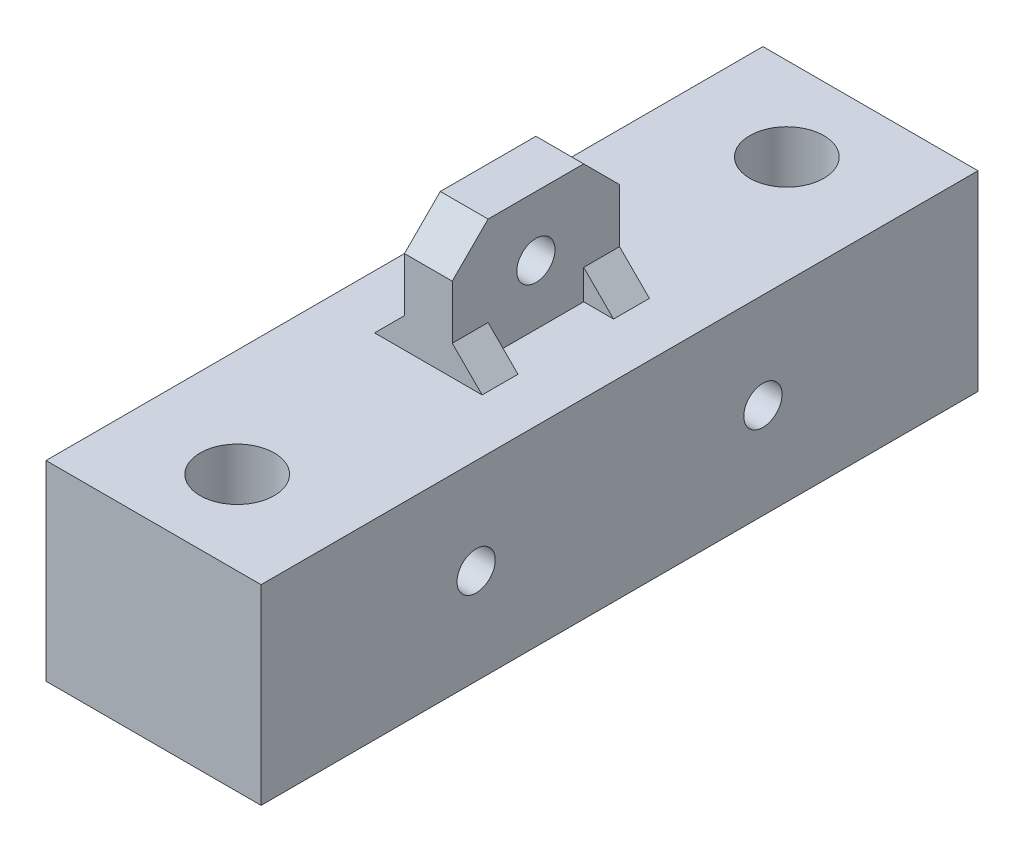
SolidWorks part; units mm, degrees
ref_plane "Front Plane" through (0, 0, 0) normal (0, 0, 1) x (1, 0, 0)
ref_plane "Top Plane" through (0, 0, 0) normal (0, 1, 0) x (1, 0, 0)
ref_plane "Right Plane" through (0, 0, 0) normal (1, 0, 0) x (0, 0, -1)
sketch "Sketch1" plane through (0, 0, 0) normal (0, 1, 0) x (1, 0, 0)
  line L1 (-9, -30) -> (9, -30)
  line L2 (-9, -30) -> (-9, 30)
  line L3 (-9, 30) -> (9, 30)
  line L4 (9, -30) -> (9, 30)
  line L5 (-9, -30) -> (9, 30) construction
  line L6 (-9, 30) -> (9, -30) construction
  point P0 (0, 0)
  dimension "D1" = 18
  dimension "D2" = 60
extrude "Boss-Extrude1" add sketch "Sketch1" along normal blind 16
sketch "Sketch2" plane through (0, 16, 0) normal (0, 1, 0) x (1, 0, 0)
  line L0 (9, 30) -> (-9, 30) construction
  line L1 (-9, -30) -> (9, -30) construction
  circle A0 centre (0, 23) radius 3.1
  circle A1 centre (0, -23) radius 3.1
  point P4 (0, 0)
  point P5 (0, 0)
  point P10 (0, 0)
  dimension "D1" = 6.2
  dimension "D2" = 6.2
  dimension "D3" = 7
  dimension "D4" = 7
extrude "Cut-Extrude1" cut sketch "Sketch2" against normal through all
sketch "Sketch3" plane through (-9, 0, 0) normal (-1, 0, 0) x (0, 0, 1)
  line L0 (-30, 0) -> (30, 0) construction
  line L1 (-30, 16) -> (-30, 0) construction
  line L3 (30, 16) -> (30, 0) construction
  circle A0 centre (-12, 8) radius 1.6
  circle A1 centre (12, 8) radius 1.6
  point P4 (0, 0)
  point P9 (-30.3857, 11.9209)
  dimension "D3" = 3.2
  dimension "D4" = 3.2
  dimension "D5" = 18
  dimension "D1" = 8
  dimension "D2" = 18
extrude "Cut-Extrude2" cut sketch "Sketch3" against normal through all
sketch "Sketch4" plane through (0, 16, 0) normal (0, 1, 0) x (1, 0, 0)
  line L1 (-2, -7) -> (2, -7)
  line L2 (-2, -7) -> (-2, 7)
  line L3 (-2, 7) -> (2, 7)
  line L4 (2, -7) -> (2, 7)
  line L5 (-2, -7) -> (2, 7) construction
  line L6 (-2, 7) -> (2, -7) construction
  point P0 (0, 0)
  dimension "D1" = 14
  dimension "D2" = 4
extrude "Boss-Extrude2" add sketch "Sketch4" along normal blind 10 contours L3 L4 L1 L2
sketch "Sketch5" plane through (-2, 0, 0) normal (-1, 0, 0) x (0, 0, 1)
  line L0 (7, 26) -> (-7, 26) construction
  circle A0 centre (0, 21) radius 1.6
  point P4 (0, 0)
  dimension "D1" = 3.2
  dimension "D2" = 5
extrude "Cut-Extrude3" cut sketch "Sketch5" against normal through all
chamfer "Chamfer1" distance 3 angle 45 2 edges at (0, 26, -7) (0, 26, 7)
sketch "Sketch6" plane through (0, 0, 7) normal (0, 0, 1) x (1, 0, 0)
  line L0 (-2, 18.5) -> (-4.5, 16)
  line L1 (-2, 23) -> (-2, 16) construction
  line L2 (-9, 16) -> (9, 16) construction
  line L3 (-4.5, 16) -> (-2, 16)
  line L4 (-2, 16) -> (-2, 18.5)
  line L5 (2, 18.5) -> (4.5, 16)
  line L6 (2, 23) -> (2, 16) construction
  line L7 (4.5, 16) -> (2, 16)
  line L8 (2, 16) -> (2, 18.5)
  dimension "D1" = 2.5
  dimension "D2" = 2.5
  dimension "D3" = 2.5
  dimension "D4" = 2.5
extrude "Boss-Extrude3" add sketch "Sketch6" against normal blind 3
sketch "Sketch7" plane through (0, 0, -7) normal (0, 0, -1) x (-1, 0, 0)
  line L3 (2, 18.5) -> (2, 16)
  line L4 (2, 16) -> (4.5, 16)
  line L5 (4.5, 16) -> (2, 18.5)
  line L6 (2, 18.5) -> (2, 16)
  line L7 (2, 16) -> (4.5, 16)
  line L8 (4.5, 16) -> (2, 18.5)
  line L9 (-2, 16) -> (-2, 18.5)
  line L10 (-2, 18.5) -> (-4.5, 16)
  line L11 (-4.5, 16) -> (-2, 16)
  line L12 (-2, 16) -> (-2, 18.5)
  line L13 (-2, 18.5) -> (-4.5, 16)
  line L14 (-4.5, 16) -> (-2, 16)
  dimension "D1" = 0
  dimension "D2" = 0
extrude "Boss-Extrude4" add sketch "Sketch7" against normal blind 3
